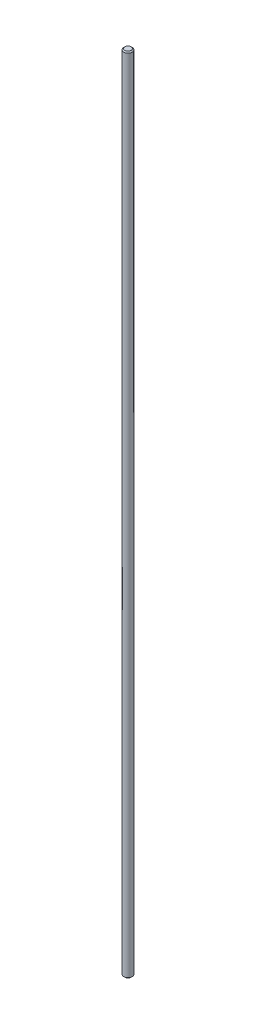
SolidWorks part; units mm, degrees
ref_plane "前视基准面" through (0, 0, 0) normal (0, 0, 1) x (1, 0, 0)
ref_plane "上视基准面" through (0, 0, 0) normal (0, 1, 0) x (1, 0, 0)
ref_plane "右视基准面" through (0, 0, 0) normal (1, 0, 0) x (0, 0, -1)
sketch "草图1" plane through (0, 0, 0) normal (0, 1, 0) x (1, 0, 0)
  circle A0 centre (0, 0) radius 4
  dimension "D1" = 8
extrude "凸台-拉伸1" add sketch "草图1" along normal blind 770
cosmetic thread "装饰螺纹线1" parameters "D2"=6.647
chamfer "倒角1" distance 1 angle 45 2 edges at (0, 0, 4) (0, 770, 4)
